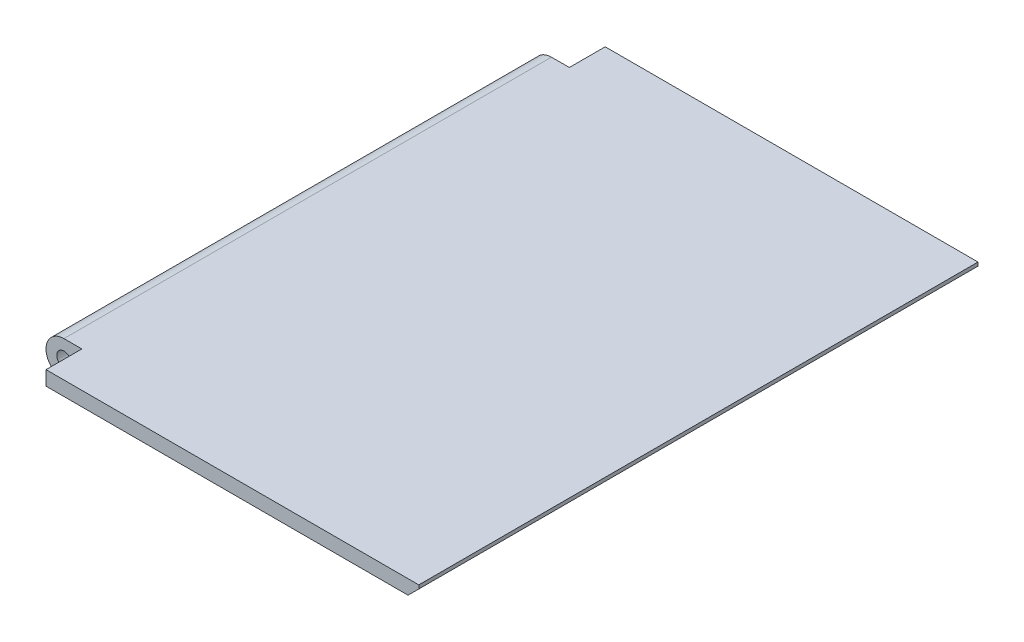
SolidWorks part; units mm, degrees
ref_plane "Front Plane" through (0, 0, 0) normal (0, 0, 1) x (1, 0, 0)
ref_plane "Top Plane" through (0, 0, 0) normal (0, 1, 0) x (1, 0, 0)
ref_plane "Right Plane" through (0, 0, 0) normal (1, 0, 0) x (0, 0, -1)
sketch "Sketch1" plane through (0, 0, 0) normal (0, 0, 1) x (1, 0, 0)
  line L5 (0, 5) -> (109, 5)
  line L7 (4.899, 1) -> (109, 1)
  line L8 (109, 5) -> (109, 1)
  arc A0 (0, 5) -> (4.899, 1) centre (0, 0) ccw
  circle A1 centre (0, 0) radius 2
extrude "Boss-Extrude1" add sketch "Sketch1" along normal blind 136
sketch "Sketch2" plane through (0, 0, 136) normal (0, 0, 1) x (1, 0, 0)
  line L0 (5, 1) -> (5, 5)
  line L1 (109, 1) -> (5, 1)
  line L2 (109, 1) -> (109, 5)
  line L3 (109, 5) -> (5, 5)
  line L5 (4.899, 1) -> (109, 1)
  line L7 (5, 5) -> (109, 5)
  line L8 (109, 1) -> (109, 5)
  line L9 (109, 5) -> (4.899, 5)
  line L10 (109, 5) -> (109, 1)
extrude "Boss-Extrude2" add sketch "Sketch2" along normal blind 10
sketch "Sketch3" plane through (0, 0, 0) normal (0, 0, -1) x (-1, 0, 0)
  line L1 (-109, 5) -> (-5, 5)
  line L2 (-109, 5) -> (-109, 1)
  line L3 (-109, 1) -> (-5, 1)
  line L5 (-109, 5) -> (-5, 5)
  line L6 (-109, 5) -> (-109, 1)
  line L8 (-5, 5) -> (-5, 1)
  line M6 (0, 5) -> (-109, 5)
  line M7 (-109, 5) -> (-109, 1)
  line M8 (-109, 1) -> (-4.899, 1)
extrude "Boss-Extrude3" add sketch "Sketch3" along normal blind 10 contours L8 M6 M7 M8
sketch "Sketch4" plane through (0, 0, 136) normal (0, 0, 1) x (1, 0, 0)
  circle A0 centre (0, 0) radius 2
sketch "Sketch5" plane through (0, 0, 146) normal (0, 0, 1) x (1, 0, 0)
  line L0 (106, 1) -> (109, 4)
  line L1 (106, 1) -> (109, 1)
  line L2 (109, 1) -> (109, 4)
extrude "Cut-Extrude2" cut sketch "Sketch5" against normal through all contours L2 L0 L1
